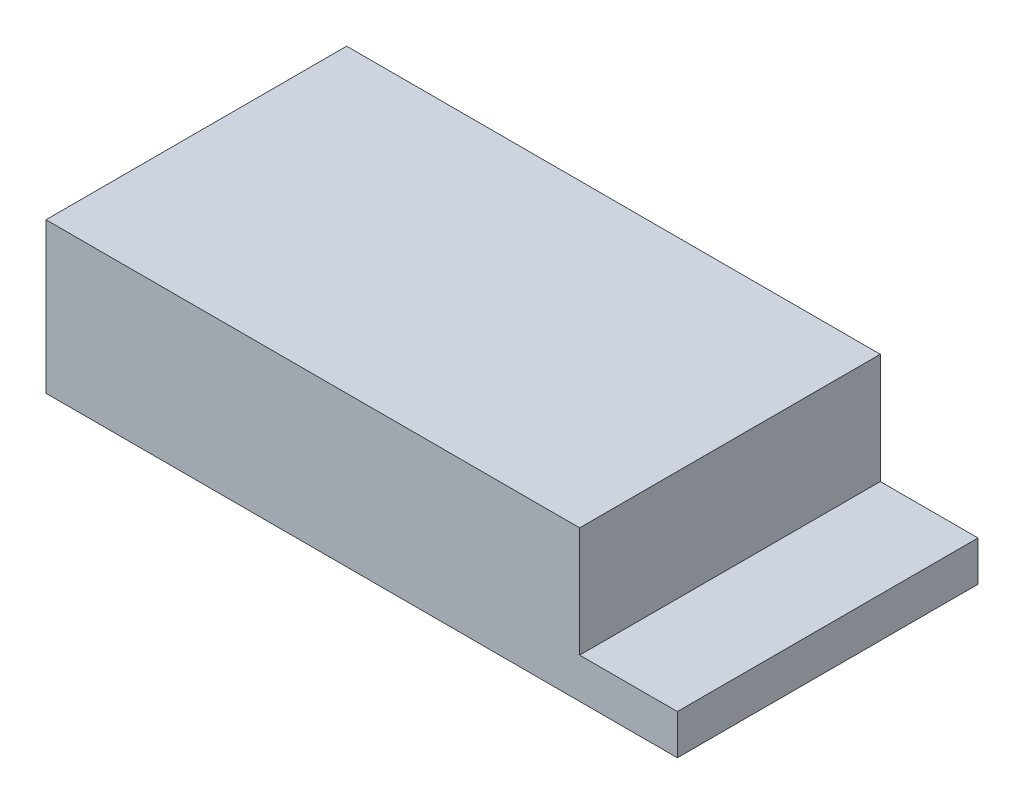
SolidWorks part; units mm, degrees
ref_plane "Front Plane" through (0, 0, 0) normal (0, 0, 1) x (1, 0, 0)
ref_plane "Top Plane" through (0, 0, 0) normal (0, 1, 0) x (1, 0, 0)
ref_plane "Right Plane" through (0, 0, 0) normal (1, 0, 0) x (0, 0, -1)
sketch "Sketch1" plane through (0, 0, 0) normal (0, 1, 0) x (1, 0, 0)
  line L1 (-630, -300) -> (630, -300)
  line L2 (-630, -300) -> (-630, 300)
  line L3 (-630, 300) -> (630, 300)
  line L4 (630, -300) -> (630, 300)
  line L5 (-630, -300) -> (630, 300) construction
  line L6 (-630, 300) -> (630, -300) construction
  point P0 (0, 0)
  dimension "D1" = 1260
  dimension "D2" = 600
extrude "Boss-Extrude1" add sketch "Sketch1" along normal blind 300
sketch "Sketch2" plane through (0, 300, 0) normal (0, 1, 0) x (1, 0, 0)
  line L0 (435, 300) -> (435, -300)
  line L1 (630, 300) -> (-630, 300) construction
  line L2 (-630, -300) -> (630, -300) construction
  line L3 (435, -300) -> (630, -300)
  line L4 (630, -300) -> (630, 300)
  line L5 (630, 300) -> (435, 300)
  dimension "D1" = 195
extrude "Cut-Extrude1" cut sketch "Sketch2" against normal blind 220
